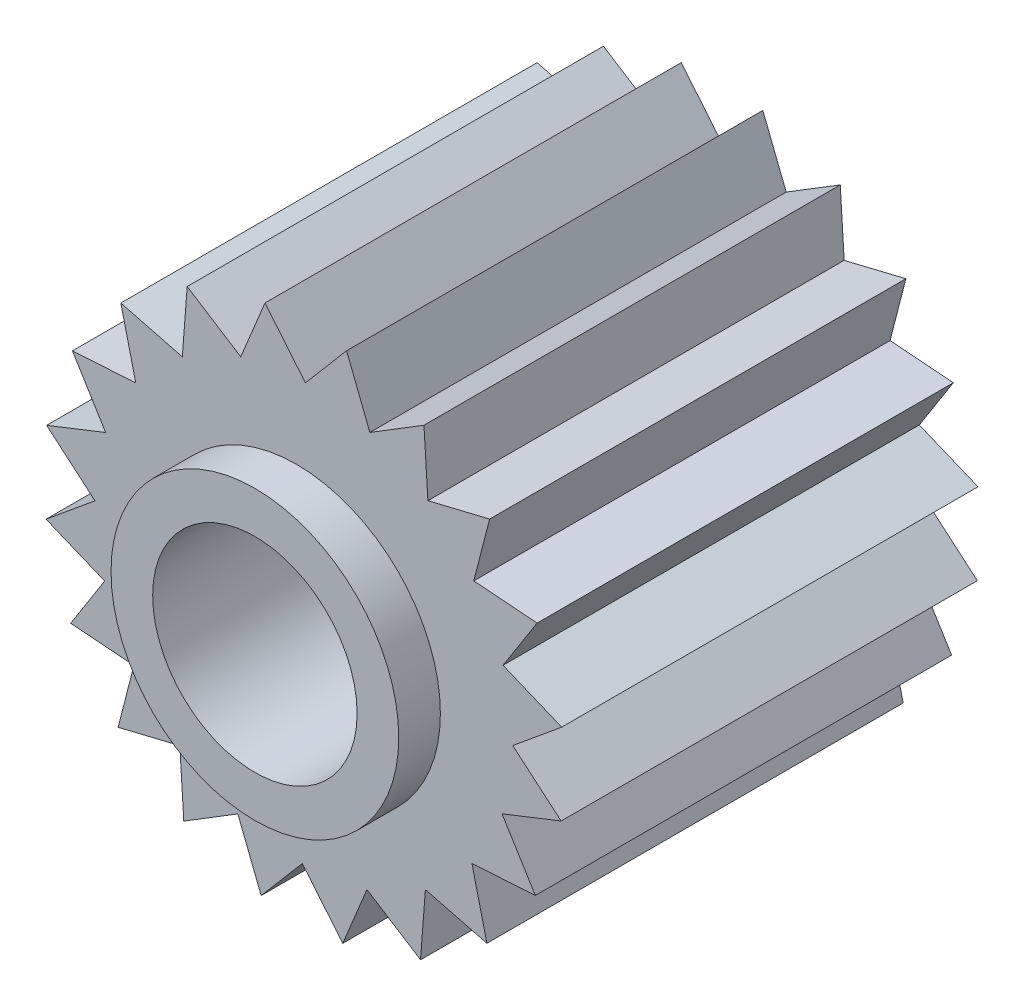
SolidWorks part; units mm, degrees
ref_plane "Front Plane" through (0, 0, 0) normal (0, 0, 1) x (1, 0, 0)
ref_plane "Top Plane" through (0, 0, 0) normal (0, 1, 0) x (1, 0, 0)
ref_plane "Right Plane" through (0, 0, 0) normal (1, 0, 0) x (0, 0, -1)
sketch "Sketch1" plane through (0, 0, 0) normal (0, 0, 1) x (1, 0, 0)
  line L2 (-1.3392, 5.0227) -> (-0.7581, 6.4333)
  line L3 (-0.7581, 6.4333) -> (0.2133, 5.2569)
  line L4 (0.2133, 5.2569) -> (1.2018, 6.4188)
  line L5 (1.2018, 6.4188) -> (1.7621, 4.9998)
  line L6 (1.7621, 4.9998) -> (3.0613, 5.7994)
  line L7 (3.0613, 5.7994) -> (3.1557, 4.2768)
  line L8 (3.1557, 4.2768) -> (4.6384, 4.6358)
  line L9 (4.6384, 4.6358) -> (4.2576, 3.1585)
  line L10 (4.2576, 3.1585) -> (5.7787, 3.0417)
  line L11 (5.7787, 3.0417) -> (4.9601, 1.7544)
  line L12 (4.9601, 1.7544) -> (6.3706, 1.1733)
  line L13 (6.3706, 1.1733) -> (5.1942, 0.2019)
  line L14 (5.1942, 0.2019) -> (6.3562, -0.7866)
  line L15 (6.3562, -0.7866) -> (4.9372, -1.3469)
  line L16 (4.9372, -1.3469) -> (5.7368, -2.6461)
  line L17 (5.7368, -2.6461) -> (4.2142, -2.7405)
  line L18 (4.2142, -2.7405) -> (4.5731, -4.2232)
  line L19 (4.5731, -4.2232) -> (3.0959, -3.8424)
  line L20 (3.0959, -3.8424) -> (2.9791, -5.3635)
  line L21 (2.9791, -5.3635) -> (1.6918, -4.5448)
  line L22 (1.6918, -4.5448) -> (1.1106, -5.9554)
  line L23 (1.1106, -5.9554) -> (0.1393, -4.779)
  line L24 (0.1393, -4.779) -> (-0.8492, -5.941)
  line L25 (-0.8492, -5.941) -> (-1.4095, -4.522)
  line L26 (-1.4095, -4.522) -> (-2.7087, -5.3216)
  line L27 (-2.7087, -5.3216) -> (-2.8031, -3.7989)
  line L28 (-2.8031, -3.7989) -> (-4.2858, -4.1579)
  line L29 (-4.2858, -4.1579) -> (-3.905, -2.6806)
  line L30 (-3.905, -2.6806) -> (-5.4261, -2.5639)
  line L31 (-5.4261, -2.5639) -> (-4.6075, -1.2765)
  line L32 (-4.6075, -1.2765) -> (-6.018, -0.6954)
  line L33 (-6.018, -0.6954) -> (-4.8416, 0.2759)
  line L34 (-4.8416, 0.2759) -> (-6.0036, 1.2645)
  line L35 (-6.0036, 1.2645) -> (-4.5846, 1.8247)
  line L36 (-4.5846, 1.8247) -> (-5.3842, 3.124)
  line L37 (-5.3842, 3.124) -> (-3.8616, 3.2183)
  line L38 (-3.8616, 3.2183) -> (-4.2206, 4.701)
  line L39 (-4.2206, 4.701) -> (-2.7433, 4.3203)
  line L40 (-2.7433, 4.3203) -> (-2.6265, 5.8414)
  line L41 (-2.6265, 5.8414) -> (-1.3392, 5.0227)
  circle A1 centre (0, 0) radius 2.4558
  point P66 (0.1763, 0.2389)
  dimension "D1" = 5.315
  dimension "D2" = 20
  dimension "D3" = 1.57
extrude "Boss-Extrude2" add sketch "Sketch1" along normal blind 10
sketch "Sketch2" plane through (0, 0, 10) normal (0, 0, 1) x (1, 0, 0)
  circle A0 centre (0, 0) radius 2.4558 construction
  circle A1 centre (0, 0) radius 2.4558
  circle A2 centre (0, 0) radius 3.4558
  dimension "D1" = 1
extrude "Boss-Extrude3" add sketch "Sketch2" along normal blind 1
ref_plane "Plane1" through (0, 0, 5) normal (0, 0, 1) x (1, 0, 0)
mirror "Mirror1" about plane through (0, 0, 5) normal (0, 0, 1) of "Boss-Extrude3"
